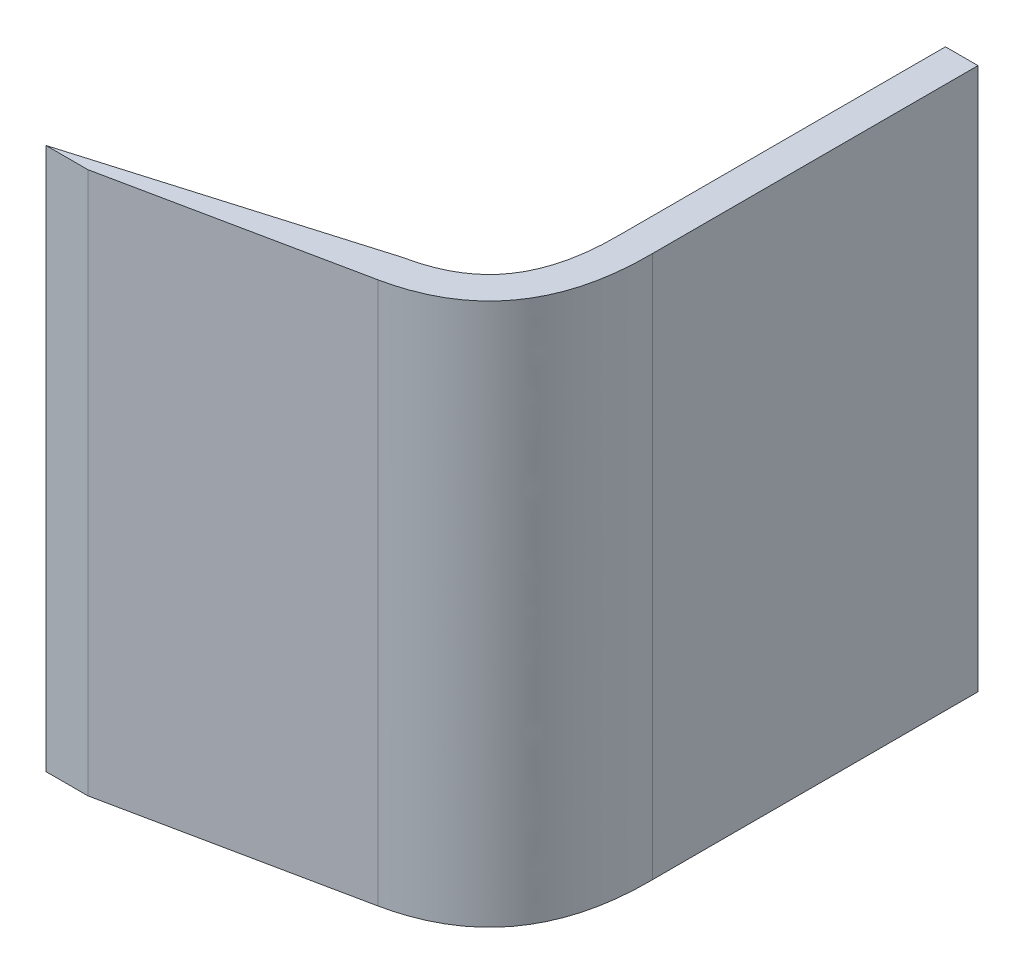
SolidWorks part; units mm, degrees
ref_plane "Front Plane" through (0, 0, 0) normal (0, 0, 1) x (1, 0, 0)
ref_plane "Top Plane" through (0, 0, 0) normal (0, 1, 0) x (1, 0, 0)
ref_plane "Right Plane" through (0, 0, 0) normal (1, 0, 0) x (0, 0, -1)
sketch "Sketch1" plane through (0, 0, 0) normal (0, 1, 0) x (1, 0, 0)
  line L0 (0, 30) -> (0, 0)
  line L2 (3, 0) -> (3, 30)
  line L3 (3, 30) -> (0, 30)
  line L4 (-8.1614, -11.8261) -> (-33.5868, -19.3412)
  line L5 (-29.7248, -19.3412) -> (-7.554, -14.764)
  line L6 (-33.5868, -19.3412) -> (-29.7248, -19.3412)
  line L7 (0.0002, -0.0334) -> (3, 0)
  line L8 (0, 0) -> (0.0002, -0.0334)
  spline S0 degree 1 poles (0.0002, -0.0334) (-8.1614, -11.8261) knots 0 0 1 1 construction
  spline S1 degree 2 poles (3, 0) (3.1399, -12.5531) (-7.554, -14.764) knots 0 0 0 1 1 1
  spline S2 degree 3 poles (0.0002, -0.0334) (0.0052, -0.4868) (-0.0095, -1.4173) (-0.1374, -3.0879) (-0.4716, -4.9478) (-1.1168, -6.7822) (-1.9737, -8.2695) (-3.0429, -9.4773) (-4.3717, -10.472) (-5.7648, -11.143) (-7.0595, -11.5706) (-7.7988, -11.7512) (-8.1614, -11.8261) knots 0 0 0 0 0.0625 0.125 0.25 0.375 0.5 0.625 0.75 0.875 0.9375 1 1 1 1
  dimension "D2" = 3
  dimension "D4" = 0.0002
  dimension "D5" = 1.6895
  dimension "D6" = 7.554
  dimension "D7" = 8.1614
  dimension "D8" = 29.7248
  dimension "D9" = 33.5868
  dimension "D10" = 19.3412
  dimension "D11" = 30
  dimension "D3" = 3
extrude "Boss-Extrude1" add sketch "Sketch1" along normal blind 50 contours L0 L8 L7 L2 L3 | L7 S2 L4 L6 L5 S1
